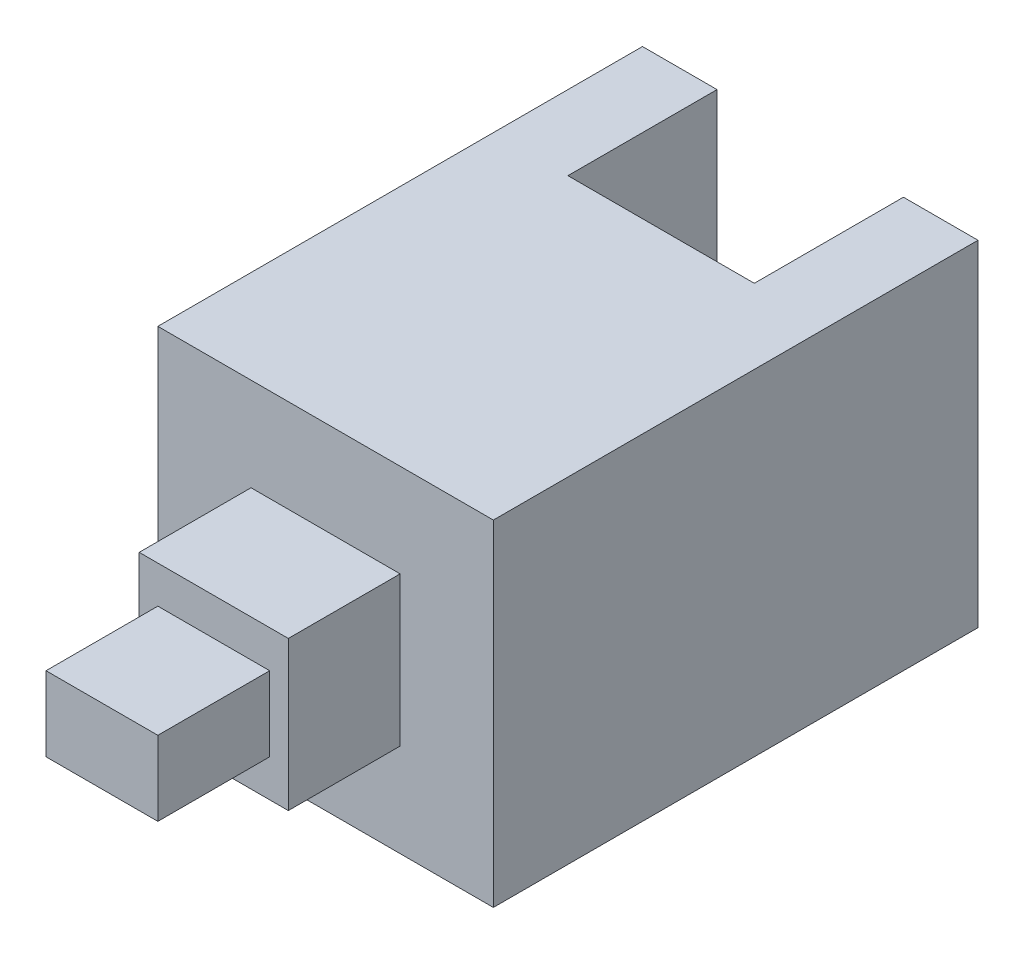
SolidWorks part; units mm, degrees
ref_plane "Front Plane" through (0, 0, 0) normal (0, 0, 1) x (1, 0, 0)
ref_plane "Top Plane" through (0, 0, 0) normal (0, 1, 0) x (1, 0, 0)
ref_plane "Right Plane" through (0, 0, 0) normal (1, 0, 0) x (0, 0, -1)
sketch "Sketch1" plane through (0, 0, 0) normal (0, 0, 1) x (1, 0, 0)
  line L1 (-4.5, 4.5) -> (4.5, 4.5)
  line L2 (-4.5, 4.5) -> (-4.5, -4.5)
  line L3 (-4.5, -4.5) -> (4.5, -4.5)
  line L4 (4.5, 4.5) -> (4.5, -4.5)
  line L5 (-4.5, 4.5) -> (4.5, -4.5) construction
  line L6 (-4.5, -4.5) -> (4.5, 4.5) construction
  point P0 (0, 0)
  dimension "D1" = 9
extrude "MAIN BODY" add sketch "Sketch1" along normal blind 9
sketch "Sketch2" plane through (0, 0, 9) normal (0, 0, 1) x (1, 0, 0)
  line L5 (-2, 2) -> (2, 2)
  line L6 (-2, 2) -> (-2, -2)
  line L7 (-2, -2) -> (2, -2)
  line L8 (2, 2) -> (2, -2)
  line L9 (-2, 2) -> (2, -2) construction
  line L10 (-2, -2) -> (2, 2) construction
  point P0 (0, 0)
  dimension "D1" = 4
extrude "Boss-Extrude2" add sketch "Sketch2" along normal blind 3
sketch "Sketch3" plane through (0, 0, 12) normal (0, 0, 1) x (1, 0, 0)
  line L1 (-1.5, 1) -> (1.5, 1)
  line L2 (-1.5, 1) -> (-1.5, -1)
  line L3 (-1.5, -1) -> (1.5, -1)
  line L4 (1.5, 1) -> (1.5, -1)
  point P4 (-1.5, 0)
  point P6 (0, 1)
  dimension "D1" = 3
  dimension "D2" = 2
extrude "Boss-Extrude3" add sketch "Sketch3" along normal blind 3
sketch "Sketch4" plane through (0, 0, 0) normal (0, 0, -1) x (-1, 0, 0)
  line L0 (-4.5, -4.5) -> (-4.5, 4.5) construction
  line L1 (-4.5, 4.5) -> (-2.5, 4.5)
  line L2 (-4.5, 4.5) -> (-4.5, -4.5)
  line L3 (-4.5, -4.5) -> (-2.5, -4.5)
  line L4 (-2.5, 4.5) -> (-2.5, -4.5)
  line L5 (-4.5, 4.5) -> (4.5, 4.5) construction
  line L6 (4.5, -4.5) -> (-4.5, -4.5) construction
  line L8 (4.5, 4.5) -> (2.5, 4.5)
  line L9 (4.5, 4.5) -> (4.5, -4.5)
  line L10 (4.5, -4.5) -> (2.5, -4.5)
  line L11 (2.5, 4.5) -> (2.5, -4.5)
  dimension "D1" = 2
extrude "PINS" add sketch "Sketch4" along normal blind 4
